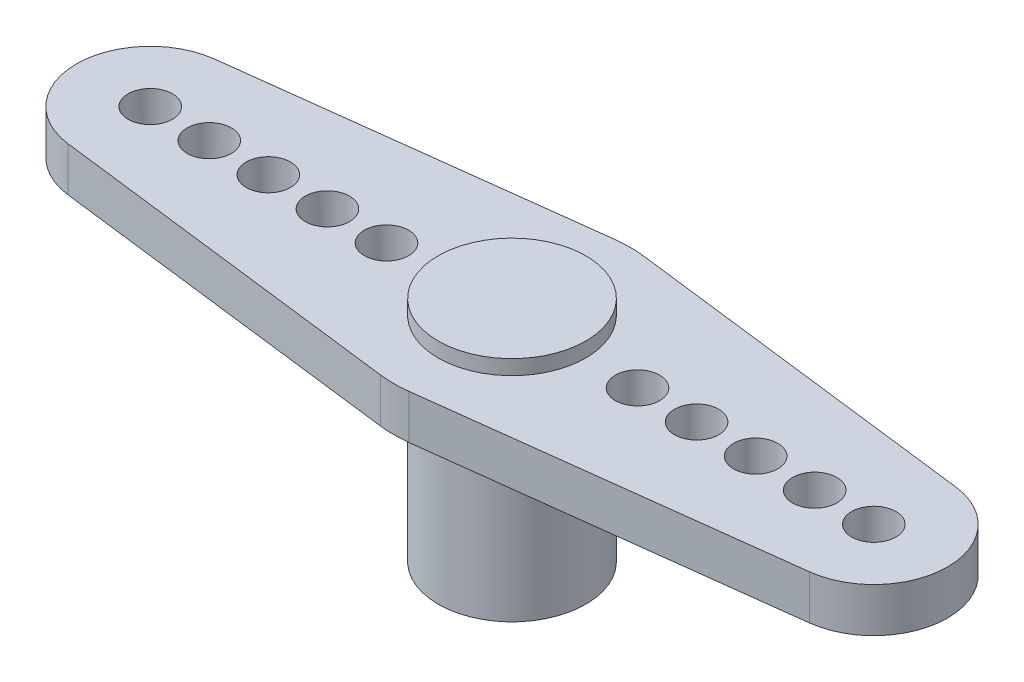
SolidWorks part; units mm, degrees
material "ABS"
ref_plane "Front Plane" through (0, 0, 0) normal (0, 0, 1) x (1, 0, 0)
ref_plane "Top Plane" through (0, 0, 0) normal (0, 1, 0) x (1, 0, 0)
ref_plane "Right Plane" through (0, 0, 0) normal (1, 0, 0) x (0, 0, -1)
sketch "Sketch2" plane through (0, 0, 0) normal (0, 1, 0) x (1, 0, 0)
  circle A0 centre (0, 0) radius 5
  dimension "D1" = 10
extrude "Boss-Extrude1" add sketch "Sketch2" along normal blind 8.44
sketch "Sketch3" plane through (0, 8.44, 0) normal (0, 1, 0) x (1, 0, 0)
  circle A0 centre (0, 0) radius 5
extrude "Boss-Extrude2" add sketch "Sketch3" along normal blind 6
sketch "Sketch4" plane through (0, 14.44, 0) normal (0, 1, 0) x (1, 0, 0)
  line L0 (0, 0) -> (0, 8) construction
  line L1 (0, 0) -> (0, -8) construction
  line L2 (0, 0) -> (29.5, 0) construction
  line L3 (0, 0) -> (-29.5, 0) construction
  line L4 (-0.9796, -7.9398) -> (-25.1122, -4.9624)
  line L5 (0.9796, 7.9398) -> (25.1122, 4.9624)
  line L6 (0.9796, -7.9398) -> (25.1122, -4.9624)
  line L7 (-0.9796, 7.9398) -> (-25.1122, 4.9624)
  arc A0 (-0.9796, 7.9398) -> (0.9796, 7.9398) centre (0, 0) cw
  arc A1 (25.1122, 4.9624) -> (25.1122, -4.9624) centre (24.5, 0) cw
  arc A2 (-0.9796, -7.9398) -> (0.9796, -7.9398) centre (0, 0) ccw
  arc A3 (-25.1122, 4.9624) -> (-25.1122, -4.9624) centre (-24.5, 0) ccw
  dimension "D3" = 5
  dimension "D1" = 8
  dimension "D2" = 29.5
extrude "Boss-Extrude3" add sketch "Sketch4" against normal blind 3
sketch "Sketch5" plane through (0, 14.44, 0) normal (0, 1, 0) x (1, 0, 0)
  line L0 (0, 0) -> (50000, 0) construction
  line L1 (0, 0) -> (0, 50000) construction
  circle A0 centre (24.5, 0) radius 1.5
  circle A1 centre (20.5, 0) radius 1.5
  circle A2 centre (16.5, 0) radius 1.5
  circle A3 centre (12.5, 0) radius 1.5
  circle A4 centre (8.5, 0) radius 1.5
  circle A5 centre (-24.5, 0) radius 1.5
  circle A6 centre (-8.5, 0) radius 1.5
  circle A7 centre (-12.5, 0) radius 1.5
  circle A8 centre (-16.5, 0) radius 1.5
  circle A9 centre (-20.5, 0) radius 1.5
  dimension "D1" = 3
  dimension "D2" = 5
extrude "Cut-Extrude1" cut sketch "Sketch5" against normal up to next
sketch "Sketch6" plane through (0, 14.44, 0) normal (0, 1, 0) x (1, 0, 0)
  circle A0 centre (0, 0) radius 5
extrude "Boss-Extrude4" add sketch "Sketch6" along normal blind 1
sketch "Sketch7" plane through (0, 0, 0) normal (1, 0, 0) x (0, 0, -1)
  line L1 (6.0178, -8.8654) -> (-6.0178, -8.8654) construction
  line L2 (6.0178, -8.8654) -> (6.0178, 8.8654) construction
  line L3 (6.0178, 8.8654) -> (-6.0178, 8.8654) construction
  line L4 (-6.0178, -8.8654) -> (-6.0178, 8.8654) construction
  line L5 (6.0178, -8.8654) -> (-6.0178, 8.8654) construction
  line L6 (6.0178, 8.8654) -> (-6.0178, -8.8654) construction
  point P0 (0, 0)
